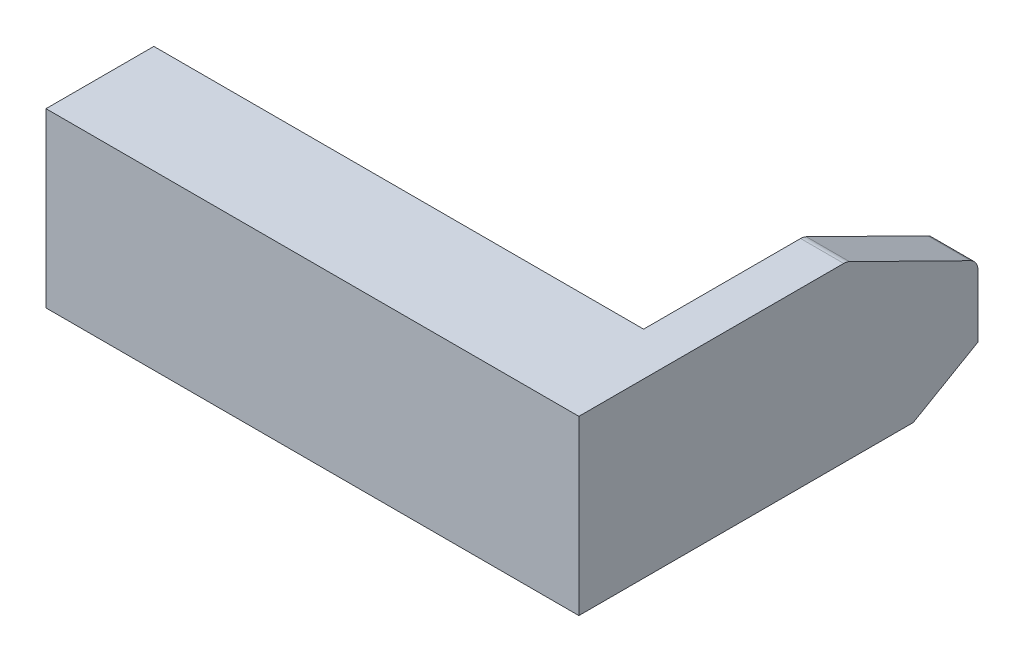
SolidWorks part; units mm, degrees
material "PLA"
ref_plane "Front Plane" through (0, 0, 0) normal (0, 0, 1) x (1, 0, 0)
ref_plane "Top Plane" through (0, 0, 0) normal (0, 1, 0) x (1, 0, 0)
ref_plane "Right Plane" through (0, 0, 0) normal (1, 0, 0) x (0, 0, -1)
sketch "Sketch1" plane through (0, 0, 0) normal (1, 0, 0) x (0, 0, -1)
  line L1 (-35.9146, 20.1296) -> (56.5854, 20.1296)
  line L2 (-35.9146, 20.1296) -> (-35.9146, -19.8704)
  line L3 (-35.9146, -19.8704) -> (56.5854, -19.8704)
  line L4 (56.5854, 20.1296) -> (56.5854, -19.8704)
  dimension "D1" = 92.5
  dimension "D2" = 40
extrude "Boss-Extrude1" add sketch "Sketch1" along normal blind 10
sketch "Sketch4" plane through (0, 0, 0) normal (-1, 0, 0) x (0, 0, 1)
  line L11 (-56.5854, 20.1296) -> (35.9146, 20.1296) construction
  line L12 (10.9146, 20.1296) -> (35.9146, 20.1296)
  line L13 (10.9146, 20.1296) -> (10.9146, -19.8704)
  line L14 (10.9146, -19.8704) -> (35.9146, -19.8704)
  line L15 (35.9146, 20.1296) -> (35.9146, -19.8704)
  line L16 (10.9146, 20.1296) -> (35.9146, -19.8704) construction
  line L17 (10.9146, -19.8704) -> (35.9146, 20.1296) construction
  line L18 (18.2896, 12.7546) -> (18.2896, -12.4954)
  line L19 (18.2896, -12.4954) -> (28.5396, -12.4954)
  line L20 (28.5396, 12.7546) -> (28.5396, -12.4954)
  line L21 (18.2896, 12.7546) -> (28.5396, 12.7546)
  point P4 (23.4146, 0.1296)
  dimension "D1" = 25
  dimension "D2" = 7.375
sketch "Sketch5" plane through (0, 0, 0) normal (-1, 0, 0) x (0, 0, 1)
  line L1 (35.9146, -19.8704) -> (-56.5854, -19.8704) construction
  line L2 (35.9146, 20.1296) -> (35.9146, -19.8704) construction
  circle A0 centre (-35.5854, 0.1296) radius 5.5
  dimension "D1" = 11
  dimension "D2" = 20
  dimension "D3" = 71.5
extrude "Cut-Extrude1" cut sketch "Sketch5" against normal blind 8.5
extrude "Boss-Extrude7" add sketch "Sketch4" along normal blind 113.5
fillet "Fillet1" radius 3 4 edges at (-113.5, -12.4954, 23.4146) (-113.5, 0.1296, 28.5396) (-113.5, 12.7546, 23.4146) (-113.5, 0.1296, 18.2896)
chamfer "Chamfer1" distance 15 angle 63.75 1 edges at (5, 20.1296, -56.5854)
fillet "Fillet3" radius 3 2 edges at (5, 20.1296, -26.1684) (5, 5.1296, -56.5854)
chamfer "Chamfer3" distance 15 angle 30 1 edges at (5, -19.8704, -56.5854)
